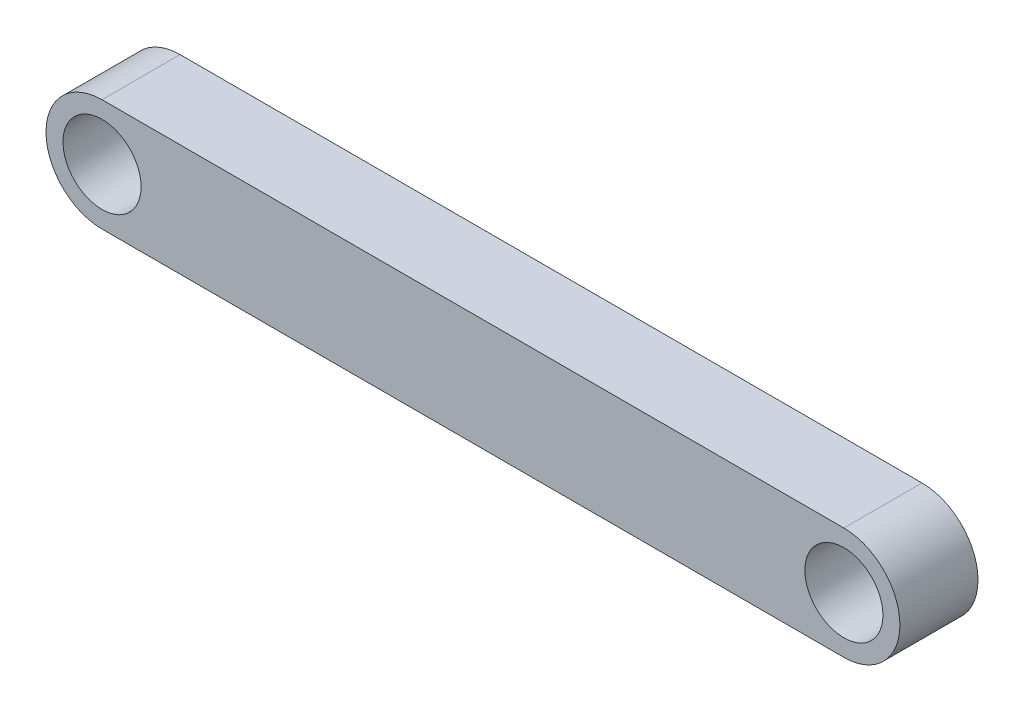
SolidWorks part; units mm, degrees
ref_plane "Front Plane" through (0, 0, 0) normal (0, 0, 1) x (1, 0, 0)
ref_plane "Top Plane" through (0, 0, 0) normal (0, 1, 0) x (1, 0, 0)
ref_plane "Right Plane" through (0, 0, 0) normal (1, 0, 0) x (0, 0, -1)
sketch "Sketch1" plane through (0, 0, 0) normal (0, 0, 1) x (1, 0, 0)
  line L0 (-9.0735, 0) -> (9.9265, 0) construction
  line L1 (-9.0735, 1.4347) -> (9.9265, 1.4347)
  line L2 (-9.0735, -1.4347) -> (9.9265, -1.4347)
  arc A0 (-9.0735, 1.4347) -> (-9.0735, -1.4347) centre (-9.0735, 0) ccw
  arc A1 (9.9265, -1.4347) -> (9.9265, 1.4347) centre (9.9265, 0) ccw
  circle A2 centre (9.9265, 0) radius 1
  circle A3 centre (-9.0735, 0) radius 1
  point P3 (0.4265, 0)
  dimension "D1" = 19
extrude "Boss-Extrude1" add sketch "Sketch1" along normal blind 2
